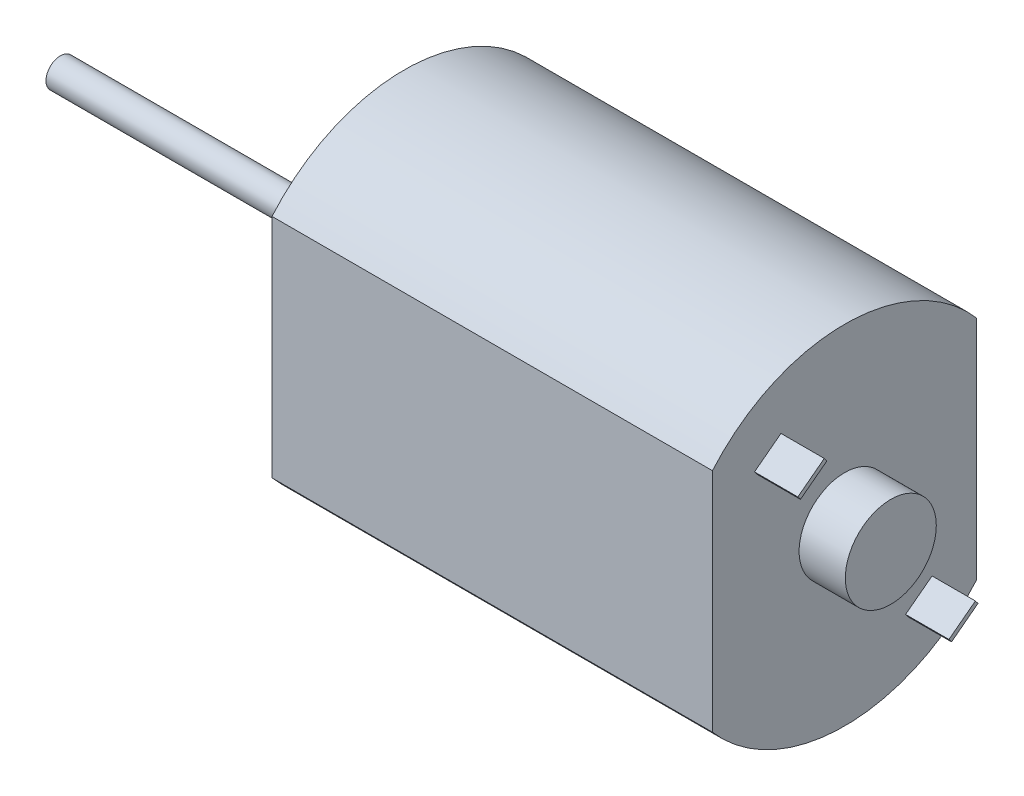
SolidWorks part; units mm, degrees
ref_plane "前视基准面" through (0, 0, 0) normal (0, 0, 1) x (1, 0, 0)
ref_plane "上视基准面" through (0, 0, 0) normal (0, 1, 0) x (1, 0, 0)
ref_plane "右视基准面" through (0, 0, 0) normal (1, 0, 0) x (0, 0, -1)
other "Configuration Table"
sketch "草图1" plane through (0, 0, 0) normal (1, 0, 0) x (0, 0, -1)
  line L1 (-9.15, -12.05) -> (9.15, -12.05)
  line L2 (-9.15, -12.05) -> (-9.15, 12.05)
  line L3 (-9.15, 12.05) -> (9.15, 12.05)
  line L4 (9.15, -12.05) -> (9.15, 12.05)
  line L5 (-9.15, -12.05) -> (9.15, 12.05) construction
  line L6 (-9.15, 12.05) -> (9.15, -12.05) construction
  circle A0 centre (0, 0) radius 12.05
  point P0 (0, 0)
  dimension "D1" = 18.3
  dimension "D2" = 24.1
extrude "凸台-拉伸1" add sketch "草图1" along normal blind 30.5 contours L4 A0 L2
sketch "草图2" plane through (0, 0, 0) normal (-1, 0, 0) x (0, 0, 1)
  circle A0 centre (0, 0) radius 3.1
  dimension "D1" = 6.2
extrude "凸台-拉伸2" add sketch "草图2" along normal blind 1.5
sketch "草图3" plane through (-1.5, 0, 0) normal (-1, 0, 0) x (0, 0, 1)
  circle A0 centre (0, 0) radius 1
  dimension "D1" = 2
extrude "凸台-拉伸3" add sketch "草图3" along normal blind 23.8 from surface at -1.5 contours A0 starting at face at (0, 0, 3.1)
sketch "草图5" plane through (30.5, 0, 0) normal (1, 0, 0) x (0, 0, -1)
  circle A0 centre (0, 0) radius 3.15
  dimension "D1" = 6.3
extrude "凸台-拉伸4" add sketch "草图5" along normal blind 3.2
sketch "草图6" plane through (30.5, 0, 0) normal (1, 0, 0) x (0, 0, -1)
  line L0 (-5.3218, 7.0085) -> (5.3218, -7.0085) construction
  line L2 (9.15, -7.8409) -> (9.15, 7.8409) construction
  line L3 (-6.0562, 6.0741) -> (-4.2245, 7.465)
  line L4 (-6.0562, 6.0741) -> (-6.2377, 6.313)
  line L5 (-6.2377, 6.313) -> (-4.4059, 7.7039)
  line L6 (-4.2245, 7.465) -> (-4.4059, 7.7039)
  line L7 (-9.15, -12.05) -> (9.15, -12.05) construction
  line L8 (6.2377, -6.313) -> (4.4059, -7.7039)
  line L9 (6.2377, -6.313) -> (6.0562, -6.0741)
  line L10 (6.0562, -6.0741) -> (4.2245, -7.465)
  line L11 (4.4059, -7.7039) -> (4.2245, -7.465)
  line L12 (-9.15, -12.05) -> (-9.15, 12.05) construction
  line L13 (-9.15, 12.05) -> (9.15, 12.05) construction
  line L14 (9.15, -12.05) -> (9.15, 12.05) construction
  line L15 (-9.15, -12.05) -> (9.15, 12.05) construction
  line L16 (-9.15, 12.05) -> (9.15, -12.05) construction
  arc A0 (9.15, 7.8409) -> (-9.15, 7.8409) centre (0, 0) ccw construction
  point P7 (0, 0)
  dimension "D1" = 17.6
  dimension "D2" = 0.3
  dimension "D3" = 2.3
extrude "凸台-拉伸5" add sketch "草图6" along normal blind 3
